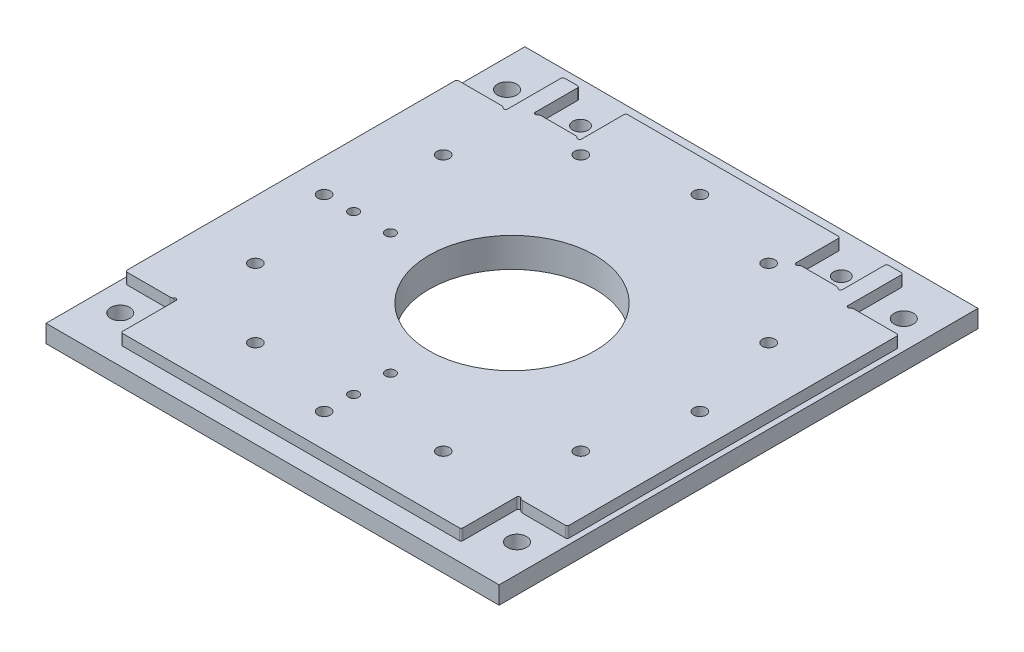
SolidWorks part; units mm, degrees
ref_plane "Front Plane" through (0, 0, 0) normal (0, 0, 1) x (1, 0, 0)
ref_plane "Top Plane" through (0, 0, 0) normal (0, 1, 0) x (1, 0, 0)
ref_plane "Right Plane" through (0, 0, 0) normal (1, 0, 0) x (0, 0, -1)
other "Configuration Table"
sketch "草图1" plane through (0, 0, 0) normal (0, 1, 0) x (1, 0, 0)
  line L1 (-60, 60) -> (60, 60)
  line L2 (-60, 60) -> (-60, -60)
  line L3 (-60, -60) -> (60, -60)
  line L4 (60, 60) -> (60, -60)
  line L5 (-60, 60) -> (60, -60) construction
  line L6 (-60, -60) -> (60, 60) construction
  point P0 (0, 0)
extrude "凸台-拉伸1" add sketch "草图1" along normal blind 3
sketch "草图2" plane through (0, 0, 0) normal (0, -1, 0) x (1, 0, 0)
  line L0 (-60, 60) -> (60, 60) construction
  line L1 (-61.5, 64) -> (61.5, 64)
  line L2 (-61.5, 64) -> (-61.5, -64)
  line L3 (-61.5, -64) -> (61.5, -64)
  line L4 (61.5, 64) -> (61.5, -64)
  line L5 (-61.5, 64) -> (61.5, -64) construction
  line L6 (-61.5, -64) -> (61.5, 64) construction
  line L7 (60, 60) -> (60, -60) construction
  point P0 (0, 0)
  dimension "D1" = 4
  dimension "D2" = 1.5
extrude "凸台-拉伸2" add sketch "草图2" along normal blind 5
sketch "草图4" plane through (0, 3, 0) normal (0, 1, 0) x (1, 0, 0)
  circle A0 centre (0, 0) radius 22.5
extrude "切除-拉伸2" cut sketch "草图4" against normal through all
sketch "草图5" plane through (0, 3, 0) normal (0, 1, 0) x (1, 0, 0)
  line L0 (-46.2, 64) -> (-46.2, 45)
  line L1 (41.7, 48) -> (29.1, 48)
  line L2 (-61.5, 64) -> (61.5, 64) construction
  line L3 (-46.2, 45) -> (-61.5, 45)
  line L4 (-61.5, -64) -> (-61.5, 64) construction
  line L5 (-61.5, 45) -> (-61.5, 64)
  line L6 (-61.5, 64) -> (-46.2, 64)
  line L7 (46.2, 64) -> (46.2, 45)
  line L8 (46.2, 45) -> (61.5, 45)
  line L9 (61.5, 64) -> (61.5, -64) construction
  line L10 (61.5, 45) -> (61.5, 64)
  line L11 (61.5, 64) -> (46.2, 64)
  line L12 (-41.7, 64) -> (-41.7, 48)
  line L13 (-41.7, 48) -> (-29.1, 48)
  line L14 (-29.1, 48) -> (-29.1, 64)
  line L15 (-29.1, 64) -> (-41.7, 64)
  line L16 (41.7, 64) -> (41.7, 48)
  line L17 (29.1, 48) -> (29.1, 64)
  line L18 (29.1, 64) -> (41.7, 64)
  line L19 (-61.5, -45) -> (-46.2, -45)
  line L20 (-46.2, -45) -> (-46.2, -64)
  line L21 (61.5, -64) -> (-61.5, -64) construction
  line L22 (-61.5, -45) -> (-61.5, -64)
  line L23 (-61.5, -64) -> (-46.2, -64)
  line L24 (46.2, -64) -> (46.2, -45)
  line L25 (46.2, -45) -> (61.5, -45)
  line L26 (61.5, -45) -> (61.5, -64)
  line L27 (61.5, -64) -> (46.2, -64)
  dimension "D1" = 4.5
  dimension "D2" = 4.5
extrude "切除-拉伸3" cut sketch "草图5" against normal blind 3
sketch "草图3" plane through (0, 3, 0) normal (0, 1, 0) x (1, 0, 0)
  line L0 (0, 0) -> (0, 51) construction
  circle A12 centre (0, 51) radius 1.7
  circle A13 centre (25.5, 44.1673) radius 1.7
  circle A14 centre (44.1673, 25.5) radius 1.7
  circle A15 centre (51, 0) radius 1.7
  circle A16 centre (44.1673, -25.5) radius 1.7
  circle A17 centre (25.5, -44.1673) radius 1.7
  circle A18 centre (0, -51) radius 1.7
  circle A19 centre (-25.5, -44.1673) radius 1.7
  circle A20 centre (-44.1673, -25.5) radius 1.7
  circle A21 centre (-51, 0) radius 1.7
  circle A22 centre (-44.1673, 25.5) radius 1.7
  circle A23 centre (-25.5, 44.1673) radius 1.7
  point P28 (0, 0)
  point P29 (0, 0)
  dimension "D1" = 12
extrude "切除-拉伸5" cut sketch "草图3" against normal through all
sketch "草图15" plane through (0, 3, 0) normal (0, 1, 0) x (1, 0, 0)
  line L0 (0, 0) -> (0, -33) construction
  line L1 (0, -33) -> (0, -43)
  line L2 (-33, 0) -> (-43, 0)
  circle A0 centre (0, -33) radius 1.35
  circle A1 centre (0, -43) radius 1.35
  circle A2 centre (-33, 0) radius 1.35
  circle A3 centre (-43, 0) radius 1.35
  point P13 (0, 0)
  dimension "D1" = 2
extrude "切除-拉伸7" cut sketch "草图15" against normal through all
sketch "草图20" plane through (0, 3, 0) normal (0, 1, 0) x (1, 0, 0)
  line L0 (-46.2, 60) -> (-46.2, 45) construction
  line L1 (-46.2, 52.5) -> (-61.5, 52.5) construction
  line L2 (-61.5, -64) -> (-61.5, 64) construction
  line L3 (-41.7, 60) -> (-41.7, 48) construction
  line L4 (-41.7, 54) -> (-29.1, 54) construction
  line L5 (-29.1, 48) -> (-29.1, 60) construction
  line L6 (41.7, 60) -> (41.7, 48) construction
  line L7 (46.2, 60) -> (46.2, 45) construction
  line L8 (41.7, 54) -> (29.1, 54) construction
  line L9 (29.1, 60) -> (29.1, 48) construction
  line L11 (61.5, 64) -> (61.5, -64) construction
  line L12 (-46.2, -45) -> (-46.2, -60) construction
  line L13 (-46.2, -52.5) -> (-61.5, -52.5) construction
  line L14 (46.2, -45) -> (46.2, -60) construction
  line L15 (46.2, -52.5) -> (61.5, -52.5) construction
  line L18 (46.2, 52.5) -> (61.5, 52.5) construction
  circle A0 centre (-53.85, 52.5) radius 2.6
  circle A4 centre (-53.85, -52.5) radius 2.6
  circle A5 centre (53.85, -52.5) radius 2.6
  circle A8 centre (53.85, 52.5) radius 2.6
  circle A9 centre (-35.4, 54) radius 2.1
  circle A10 centre (35.4, 54) radius 2.1
extrude "切除-拉伸14" cut sketch "草图20" against normal through all
sketch "草图21" plane through (0, -5, 0) normal (0, -1, 0) x (1, 0, 0)
  circle A0 centre (53.85, -52.5) radius 5.5
  circle A1 centre (35.4, -54) radius 4.6
  circle A2 centre (-35.4, -54) radius 4.6
  circle A3 centre (-53.85, -52.5) radius 5.5
  circle A4 centre (-53.85, 52.5) radius 5.5
  circle A5 centre (53.85, 52.5) radius 5.5
extrude "切除-拉伸15" cut sketch "草图21" against normal blind 1
sketch "草图23" plane through (-61.5, 0, 0) normal (-1, 0, 0) x (0, 0, 1)
  line L0 (-65, 0) -> (-64, 0)
  line L1 (-64, 0) -> (-64, -5)
  line L2 (-64, -5) -> (-65, -5)
  line L3 (-65, -5) -> (-65, 0)
  line L4 (65, 0) -> (65, -5)
  line L5 (65, -5) -> (64, -5)
  line L6 (64, -5) -> (-64, -5) construction
  line L7 (64, -5) -> (64, 0)
  line L8 (64, 0) -> (65, 0)
  point P2 (0, 0)
extrude "凸台-拉伸5" add sketch "草图23" against normal up to surface (123 mm away) up to face at (61.5, -2.5, 0)
fillet "圆角1" radius 0.5 12 edges at (60, 1.5, 45) (46.2, 1.5, 60) (-46.2, 1.5, 60) (-60, 1.5, 45) (60, 1.5, -45) (46.2, 1.5, -60) (41.7, 1.5, -60) (29.1, 1.5, -60) (-29.1, 1.5, -60) (-41.7, 1.5, -60) (-60, 1.5, -45) (-46.2, 1.5, -60)
sketch "草图24" plane through (0, -5, 0) normal (0, -1, 0) x (-1, 0, 0)
  circle A0 centre (0, 0) radius 57.5
split line "分割线1"
sketch "草图25" plane through (0, 3, 0) normal (0, 1, 0) x (1, 0, 0)
  line L0 (-46.2, 45) -> (-46.7, 45) construction
  line L1 (-59.5, 45) -> (-46.2, 45) construction
  line L2 (-41.7, 48) -> (-41.2, 48) construction
  line L3 (-41.7, 48) -> (-29.1, 48) construction
  line L4 (-29.1, 48) -> (-29.6, 48) construction
  line L5 (29.1, 48) -> (41.7, 48) construction
  line L6 (41.7, 48) -> (41.2, 48) construction
  line L7 (46.2, 45) -> (46.7, 45) construction
  line L8 (46.2, 45) -> (59.5, 45) construction
  line L9 (-46.2, -45) -> (-46.7, -45) construction
  line L10 (29.1, 48) -> (29.6, 48) construction
  line L11 (-46.2, -45) -> (-59.5, -45) construction
  line L12 (46.2, -45) -> (46.7, -45) construction
  line L13 (59.5, -45) -> (46.2, -45) construction
  circle A0 centre (-46.7, 45) radius 0.5
  circle A1 centre (-41.2, 48) radius 0.5
  circle A3 centre (41.2, 48) radius 0.5
  circle A4 centre (46.7, 45) radius 0.5
  circle A7 centre (-46.7, -45) radius 0.5
  circle A8 centre (46.7, -45) radius 0.5
  circle A9 centre (-29.6, 48) radius 0.5
  circle A10 centre (29.6, 48) radius 0.5
extrude "切除-拉伸17" cut sketch "草图25" against normal up to surface (3 mm away) up to face at (-53.85, 0, 49.9)
fillet "圆角2" radius 1 8 edges at (-47.2, 1.5, 45) (-47.2, 1.5, -45) (-40.7, 1.5, -48) (40.7, 1.5, -48) (47.2, 1.5, -45) (47.2, 1.5, 45) (30.1, 1.5, -48) (-30.1, 1.5, -48)
chamfer "倒角1" distance 0.2 angle 45 4 edges at (0, -5, -65) (-61.5, -5, 0) (0, -5, 65) (61.5, -5, 0)
